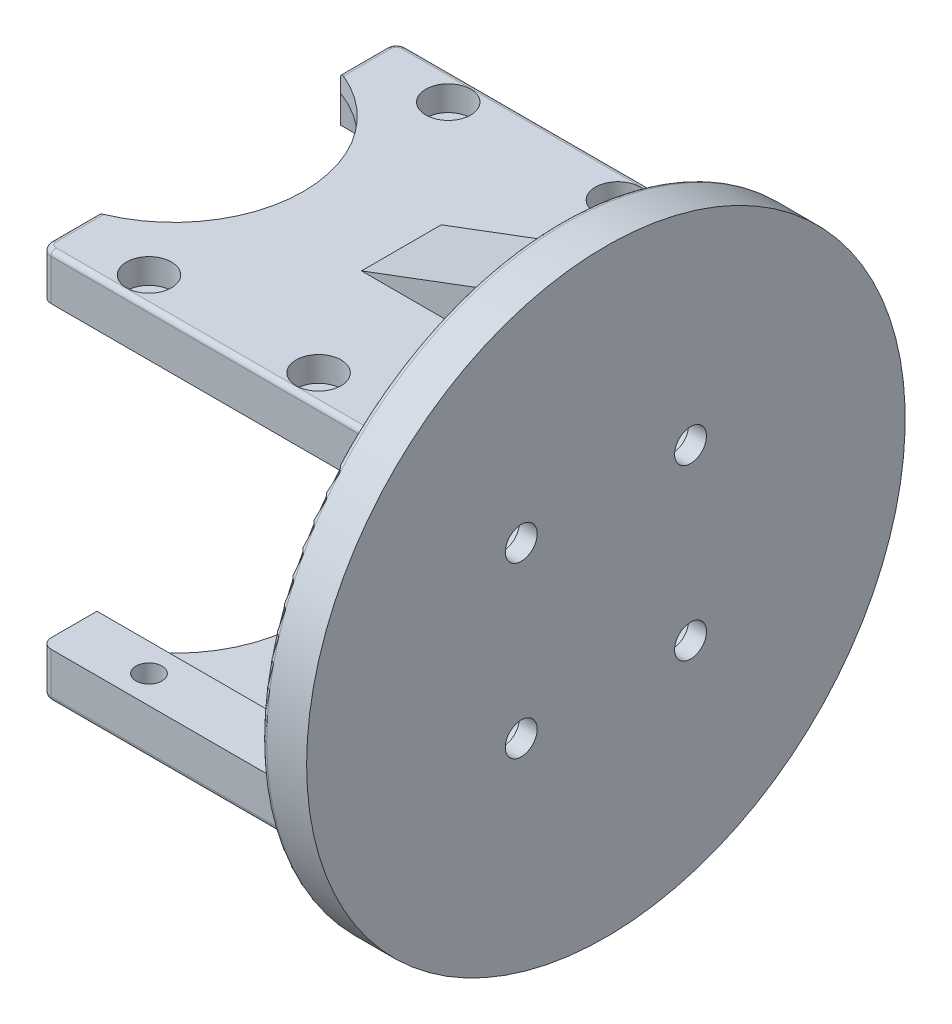
SolidWorks part; units mm, degrees
ref_plane "Front Plane" through (0, 0, 0) normal (0, 0, 1) x (1, 0, 0)
ref_plane "Top Plane" through (0, 0, 0) normal (0, 1, 0) x (1, 0, 0)
ref_plane "Right Plane" through (0, 0, 0) normal (1, 0, 0) x (0, 0, -1)
sketch "Sketch1" plane through (0, 0, 0) normal (0, 1, 0) x (1, 0, 0)
  line L0 (4.49, 12.2) -> (4.49, 17.8)
  line L1 (4.49, -12.2) -> (33.2, -12.2)
  line L3 (4.49, 12.2) -> (33.2, 12.2)
  line L4 (33.2, -12.2) -> (33.2, 12.2)
  line L5 (4.49, -17.8) -> (38.3, -17.8)
  line L6 (4.49, -17.8) -> (4.49, -12.2)
  line L7 (4.49, 17.8) -> (38.3, 17.8)
  line L8 (38.3, -17.8) -> (38.3, 17.8)
  line L9 (4.49, 17.8) -> (-12.2, 17.8) construction
  line L10 (4.49, 12.2) -> (-12.2, 12.2) construction
  line L11 (4.49, -12.2) -> (-12.2, -12.2) construction
  line L12 (4.49, -17.8) -> (-12.2, -17.8) construction
  line L13 (-12.2, 17.8) -> (-12.2, -17.8) construction
  line L14 (33.2, 0) -> (-11, 0) construction
  line L15 (38.3, 0) -> (33.2, 0) construction
  arc A0 (4.49, -12.2) -> (4.49, 12.2) centre (0, 0) ccw construction
  circle A1 centre (0, 0) radius 11 construction
  circle A2 centre (-4.5, 15) radius 1.3
  circle A3 centre (-4.5, 15) radius 2.25 construction
  circle A4 centre (12.5, 15) radius 1.3
  circle A5 centre (29.5, 15) radius 1.3
  circle A6 centre (-4.5, -15) radius 1.3
  circle A7 centre (12.5, -15) radius 1.3
  circle A8 centre (29.5, -15) radius 1.3
  circle A10 centre (35.75, -8.5) radius 1.3
  circle A11 centre (35.75, 8.5) radius 1.3
  point P16 (4.49, 15)
  point P36 (35.75, 0)
  point P37 (35.75, -6.965)
  point P38 (0, 0)
  point P39 (0, 0)
  point P40 (0, 0)
  dimension "D1" = 22
  dimension "D5" = 2.6
  dimension "D9" = 13
  dimension "D10" = 4.5
  dimension "D14" = 2.6
  dimension "D2" = 5.1
  dimension "D3" = 5.6
  dimension "D4" = 5.6
  dimension "D6" = 7.7
  dimension "D7" = 15
  dimension "D8" = 4.5
  dimension "D11" = 17
  dimension "D12" = 34
  dimension "D13" = 3.7
  dimension "D15" = 6.5
extrude "Boss-Extrude1" add sketch "Sketch1" along normal blind 2.8 contours L5 L8 L7 L0 L3 L4 L1 L6 A8 A4 A5 A7 A10 A11 | A2
sketch "Sketch2" plane through (0, 0, 0) normal (0, 1, 0) x (1, 0, 0)
  line L0 (4.49, 12.2) -> (33.2, 12.2) construction
  line L1 (4.49, -12.2) -> (33.2, -12.2) construction
  line L2 (33.2, -12.2) -> (33.2, 12.2) construction
  line L3 (4.49, 12.2) -> (33.2, 12.2)
  line L4 (4.49, -12.2) -> (33.2, -12.2)
  line L5 (33.2, -12.2) -> (33.2, 12.2)
  line L6 (4.49, -17.8) -> (4.49, -12.2) construction
  line L7 (4.49, -17.8) -> (38.3, -17.8) construction
  line L8 (38.3, -17.8) -> (38.3, 17.8) construction
  line L9 (4.49, 17.8) -> (38.3, 17.8) construction
  line L10 (4.49, 12.2) -> (4.49, 17.8) construction
  line L11 (4.49, -17.8) -> (4.49, -12.2)
  line L12 (4.49, -17.8) -> (38.3, -17.8)
  line L13 (38.3, -17.8) -> (38.3, 17.8)
  line L14 (4.49, 17.8) -> (38.3, 17.8)
  line L15 (4.49, 12.2) -> (4.49, 17.8)
  circle A0 centre (12.5, 15) radius 1.3 construction
  circle A1 centre (29.5, 15) radius 1.3 construction
  circle A2 centre (35.75, 8.5) radius 1.3 construction
  circle A3 centre (35.75, -8.5) radius 1.3 construction
  circle A4 centre (29.5, -15) radius 1.3 construction
  circle A5 centre (12.5, -15) radius 1.3 construction
  arc A6 (4.49, -12.2) -> (4.49, 12.2) centre (0, 0) ccw construction
  circle A7 centre (12.5, 15) radius 1.3
  circle A8 centre (29.5, 15) radius 1.3
  circle A9 centre (35.75, 8.5) radius 1.3
  circle A10 centre (35.75, -8.5) radius 1.3
  circle A11 centre (29.5, -15) radius 1.3
  circle A12 centre (12.5, -15) radius 1.3
  arc A13 (4.49, -12.2) -> (4.49, 12.2) centre (0, 0) ccw
extrude "Boss-Extrude2" add sketch "Sketch2" against normal blind 1.8 contours A13 L4 L5 L3 | L15 L3 L5 L4 L11 L12 L13 L14 A12 A11 A10 A9 A8 A7
sketch "Sketch3" plane through (0, -1.8, 0) normal (0, -1, 0) x (1, 0, 0)
  circle A0 centre (12.5, 15) radius 2.25
  circle A1 centre (29.5, 15) radius 2.25
  circle A2 centre (29.5, -15) radius 2.25
  circle A3 centre (12.5, -15) radius 2.25
  circle A4 centre (35.75, 8.5) radius 2.25
  circle A5 centre (35.75, -8.5) radius 2.25
  dimension "D1" = 4.5
  dimension "D4" = 17
  dimension "D5" = 4.5
  dimension "D2" = 2
  dimension "D3" = 2
extrude "Cut-Extrude1" cut sketch "Sketch3" against normal blind 2.5
sketch "Sketch4" plane through (38.3, 0, 0) normal (1, 0, 0) x (0, 0, -1)
  line L4 (-17.8, 2.8) -> (-17.8, -1.8)
  line L5 (-17.8, -1.8) -> (17.8, -1.8)
  line L6 (17.8, -1.8) -> (17.8, 2.8)
  line L7 (17.8, 2.8) -> (-17.8, 2.8)
  line L8 (-17.8, 2.8) -> (-17.8, -1.8)
  line L9 (-17.8, -1.8) -> (17.8, -1.8)
  line L10 (17.8, -1.8) -> (17.8, 2.8)
  line L11 (17.8, 2.8) -> (-17.8, 2.8)
  dimension "D1" = 0
extrude "Boss-Extrude3" add sketch "Sketch4" along normal blind 5
sketch "Sketch5" plane through (0, 2.8, 0) normal (0, 1, 0) x (1, 0, 0)
  line L0 (4.49, 17.8) -> (43.3, 17.8) construction
  line L1 (38.8, 17.8) -> (43.3, 17.8)
  line L2 (38.8, 17.8) -> (38.8, -17.8)
  line L3 (38.8, -17.8) -> (43.3, -17.8)
  line L4 (43.3, 17.8) -> (43.3, -17.8)
  dimension "D1" = 4.5
extrude "Boss-Extrude4" add sketch "Sketch5" along normal blind 15
mirror "Mirror3" about plane through (0, 17.8, 0) normal (0, 1, 0) of "Boss-Extrude4", "Boss-Extrude3", "Cut-Extrude1", "Boss-Extrude2", "Boss-Extrude1"
fillet "Fillet1" radius 1 4 edges at (4.49, 35.1, -17.8) (4.49, 0.5, -17.8) (4.49, 35.1, 17.8) (4.49, 0.5, 17.8)
sketch "Sketch9" plane through (43.3, 0, 0) normal (1, 0, 0) x (0, 0, -1)
  line L0 (17.8, -1.8) -> (17.8, 37.4) construction
  line L1 (-2.05, 21.85) -> (2.05, 21.85)
  line L2 (-4.05, 19.85) -> (-4.05, 15.75)
  line L3 (-2.05, 13.75) -> (2.05, 13.75)
  line L4 (4.05, 19.85) -> (4.05, 15.75)
  line L5 (-4.05, 21.85) -> (4.05, 13.75) construction
  line L6 (-4.05, 13.75) -> (4.05, 21.85) construction
  arc A0 (-4.05, 15.75) -> (-2.05, 13.75) centre (-2.05, 15.75) ccw
  arc A1 (2.05, 13.75) -> (4.05, 15.75) centre (2.05, 15.75) ccw
  arc A2 (2.05, 21.85) -> (4.05, 19.85) centre (2.05, 19.85) cw
  arc A3 (-2.05, 21.85) -> (-4.05, 19.85) centre (-2.05, 19.85) ccw
  point P0 (0, 17.8)
  point P5 (0, 0)
  point P7 (4.05, 17.8)
  point P10 (17.8, 17.8)
  dimension "D2" = 2
  dimension "D1" = 8.1
extrude "Cut-Extrude4" cut sketch "Sketch9" against normal blind 3.5
sketch "Sketch10" plane through (38.8, 0, 0) normal (-1, 0, 0) x (0, 0, 1)
  line L0 (-2.05, 21.85) -> (2.05, 21.85) construction
  line L1 (-17.8, -1.8) -> (-17.8, 37.4) construction
  circle A0 centre (0, 17.8) radius 30
  point P4 (0, 21.85)
  point P5 (0, 0)
  point P6 (0, 16.4225)
  point P7 (0, 17.2062)
  point P10 (-17.8, 17.8)
  dimension "D1" = 60
extrude "Boss-Extrude6" add sketch "Sketch10" against normal up to surface (4.5 mm away)
sketch "Sketch6" plane through (43.3, 0, 0) normal (1, 0, 0) x (0, 0, -1)
  line L0 (17.8, -1.8) -> (17.8, 37.4) construction
  line L1 (0, 17.8) -> (0, 33.7773) construction
  line L2 (0, 17.8) -> (-12.1542, 29.9542) construction
  circle A0 centre (0, 17.8) radius 12 construction
  circle A1 centre (-8.4853, 26.2853) radius 1.6
  circle A2 centre (8.4853, 26.2853) radius 1.6
  circle A3 centre (8.4853, 9.3147) radius 1.6
  circle A4 centre (-8.4853, 9.3147) radius 1.6
  point P2 (11.1065, 9.951)
  point P6 (17.8, 17.8)
  point P11 (0, 0)
  point P19 (0, 17.8)
  dimension "D1" = 24
  dimension "D3" = 3.2
  dimension "D2" = 45
  dimension "D4" = 4
extrude "Cut-Extrude2" cut sketch "Sketch6" against normal through all
sketch "Sketch8" plane through (38.8, 0, 0) normal (-1, 0, 0) x (0, 0, 1)
  circle A0 centre (-8.4853, 26.2853) radius 2.8
  circle A1 centre (8.4853, 26.2853) radius 2.8
  circle A2 centre (8.4853, 9.3147) radius 2.8
  circle A3 centre (-8.4853, 9.3147) radius 2.8
  dimension "D1" = 5.6
extrude "Cut-Extrude3" cut sketch "Sketch8" against normal blind 2.7
sketch "Sketch11" plane through (0, 0, 0) normal (0, 0, 1) x (1, 0, 0)
  line L0 (38.8, 43.4) -> (22.8, 37.4)
  line L1 (38.8, 47.8) -> (38.8, -12.2) construction
  line L2 (5.49, 37.4) -> (38.8, 37.4) construction
  line L4 (5.49, 37.4) -> (38.8, 37.4) construction
  point P8 (47.9636, 43.044)
  dimension "D1" = 16
  dimension "D2" = 6
rib "Rib1" sketch "Sketch11" sketch "Sketch11" thickness 8 extrusion direction parallel to sketch draft on no parameters "D1"=8
ref_plane "Plane2" through (0, 17.8, 0) normal (0, 1, 0) x (1, 0, 0)
mirror "Mirror4" about plane through (0, 17.8, 0) normal (0, 1, 0) of "Rib1"
fillet "Fillet2" radius 0.5 1 edges at (38.8, 17.8, 30)
sketch "Sketch12" plane through (43.3, 0, 0) normal (1, 0, 0) x (0, 0, -1)
  circle A1 centre (0, 17.8) radius 30
  circle A2 centre (0, 17.8) radius 30
  dimension "D1" = 0
fillet "Fillet3" radius 0.5 26 edges at (4.49, 37.4, -14.5) (22.145, -1.8, -17.8) (22.145, -1.8, 17.8) (4.49, -1.8, 14.5) (4.7829, -1.8, 17.5071) (4.7829, -1.8, -17.5071) (22.145, 37.4, -17.8) (4.49, 37.4, 14.5) (22.145, 37.4, 17.8) (4.7829, 37.4, 17.5071) (4.7829, 37.4, -17.5071) (38.8, 37.4, 10.9) (38.8, -1.8, -10.9) (38.8, 0.5, 17.8) (38.8, 35.1, 17.8) (38.8, 0.5, -17.8) (38.8, 35.1, -17.8) (38.8, 37.4, -10.9) (38.8, 43.4, 0) (38.8, 40.4, 4) (38.8, 40.4, -4) (38.8, -1.8, 10.9) (38.8, -7.8, 0) (38.8, -4.8, 4) (38.8, -4.8, -4) (4.49, -1.8, -14.5)
